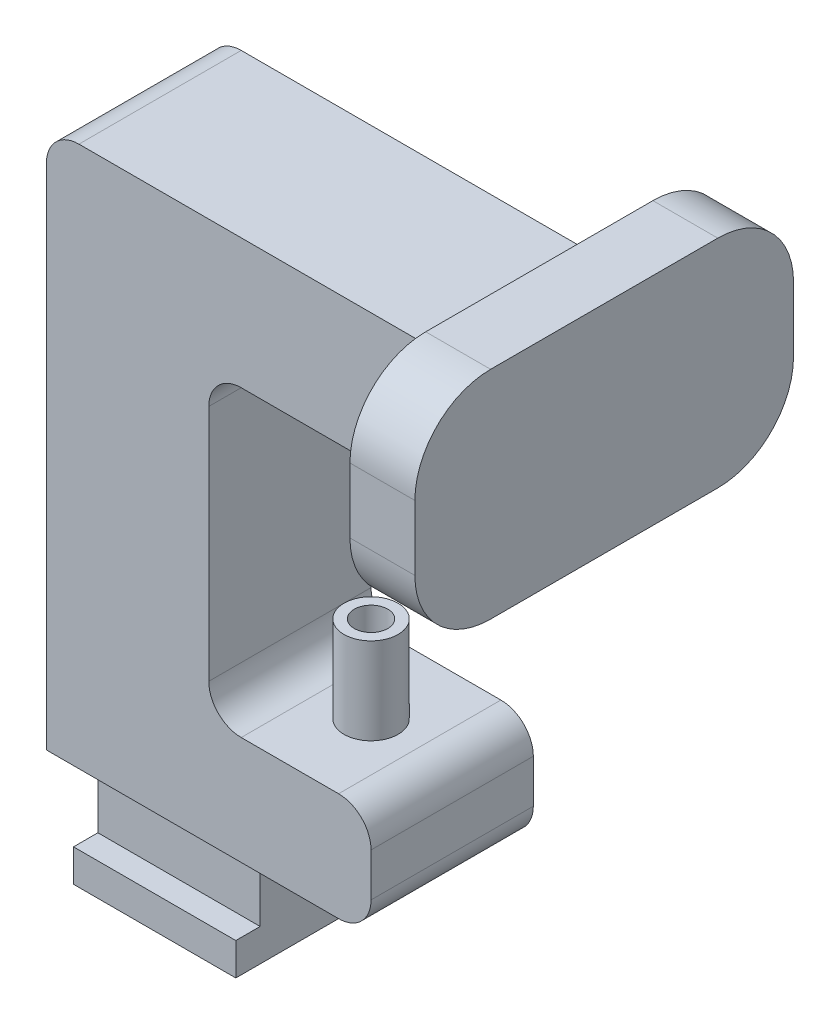
SolidWorks part; units mm, degrees
other "Markup1"
sketch "Sketch8" plane through (34.6, -62, 15) normal (0.0601, -0.0781, 0.9951) x (0.988, 0.1465, -0.0482)
ref_plane "Front Plane" through (0, 0, 0) normal (0, 0, 1) x (1, 0, 0)
ref_plane "Top Plane" through (0, 0, 0) normal (0, 1, 0) x (1, 0, 0)
ref_plane "Right Plane" through (0, 0, 0) normal (1, 0, 0) x (0, 0, -1)
sketch "Sketch1" plane through (0, 0, 0) normal (0, 0, 1) x (1, 0, 0)
  line L0 (0, 0) -> (0, -50)
  line L1 (0, -50) -> (25, -50)
  line L2 (10, 0) -> (10, -40)
  line L3 (10, -40) -> (25, -40)
  line L4 (0, 0) -> (10, 0)
  line L5 (25, -50) -> (25, -40)
  dimension "D1" = 50
  dimension "D2" = 25
  dimension "D3" = 10
extrude "Boss-Extrude1" add sketch "Sketch1" along normal blind 15
sketch "Sketch2" plane through (0, 0, 0) normal (-1, 0, 0) x (0, 0, 1)
  line L0 (7.5, 0) -> (7.5, -50) construction
  line L1 (15, 0) -> (0, 0) construction
  line L2 (15, -50) -> (0, -50) construction
  line L3 (10.25, -50) -> (4.75, -50)
  line L4 (4.75, -50) -> (4.75, -59)
  line L5 (4.75, -59) -> (2.5, -59)
  line L6 (2.5, -59) -> (2.5, -62)
  line L7 (2.5, -62) -> (8.2744, -62)
  line L8 (12.5, -62) -> (6.7256, -62)
  line L9 (10.25, -59) -> (12.5, -59)
  line L10 (12.5, -59) -> (12.5, -62)
  line L11 (10.25, -50) -> (10.25, -59)
  line M8 (0, -50) -> (15, -50)
  dimension "D1" = 5.5
  dimension "D2" = 10
  dimension "D3" = 3
  dimension "D4" = 9
extrude "Boss-Extrude2" add sketch "Sketch2" against normal blind 10 contours L11 L3 L4 L5 L6 L7 L8 L10 L9 M8
sketch "Sketch3" plane through (0, -40, 0) normal (0, 1, 0) x (1, 0, 0)
  line L0 (17.5, 0) -> (17.5, -15) construction
  line L1 (25, 0) -> (10, 0) construction
  line L2 (25, -15) -> (10, -15) construction
  line L3 (25, -7.5) -> (10, -7.5) construction
  line L4 (25, -15) -> (25, 0) construction
  line L5 (10, -15) -> (10, 0) construction
  circle A0 centre (17.5, -7.5) radius 1.55
  dimension "D1" = 3.1
extrude "Cut-Extrude1" cut sketch "Sketch3" against normal through all
sketch "Sketch4" plane through (0, -40, 0) normal (0, 1, 0) x (1, 0, 0)
  circle A0 centre (17.5, -7.5) radius 1.55 construction
  circle A1 centre (17.5, -7.5) radius 1.55
  circle A2 centre (17.5, -7.5) radius 2.5
  dimension "D1" = 5
extrude "Boss-Extrude3" add sketch "Sketch4" along normal blind 8
sketch "Sketch5" plane through (10, 0, 0) normal (1, 0, 0) x (0, 0, -1)
  line L0 (0, -40) -> (0, 0) construction
  line L1 (-15, 0) -> (0, 0)
  line L2 (-15, 0) -> (-15, -12)
  line L3 (-15, -12) -> (0, -12)
  line L4 (0, 0) -> (0, -12)
  dimension "D1" = 12
extrude "Boss-Extrude4" add sketch "Sketch5" along normal blind 23.05
sketch "Sketch7" plane through (0, 0, 0) normal (-1, 0, 0) x (0, 0, 1)
  line L12 (0, 0) -> (0, -50)
  line L13 (0, -50) -> (4.75, -50)
  line L14 (4.75, -50) -> (4.75, -59)
  line L15 (4.75, -59) -> (2.5, -59)
  line L16 (2.5, -59) -> (2.5, -62)
  line L17 (2.5, -62) -> (12.5, -62)
  line L18 (12.5, -62) -> (12.5, -59)
  line L19 (12.5, -59) -> (10.25, -59)
  line L20 (10.25, -59) -> (10.25, -50)
  line L21 (10.25, -50) -> (15, -50)
  line L22 (15, -50) -> (15, 0)
  line L23 (15, 0) -> (0, 0)
  line L24 (0, 0) -> (0, -50)
  line L25 (0, -50) -> (4.75, -50)
  line L26 (4.75, -50) -> (4.75, -59)
  line L27 (4.75, -59) -> (2.5, -59)
  line L28 (2.5, -59) -> (2.5, -62)
  line L29 (2.5, -62) -> (12.5, -62)
  line L30 (12.5, -62) -> (12.5, -59)
  line L31 (12.5, -59) -> (10.25, -59)
  line L32 (10.25, -59) -> (10.25, -50)
  line L33 (10.25, -50) -> (15, -50)
  line L34 (15, -50) -> (15, 0)
  line L35 (15, 0) -> (0, 0)
  dimension "D1" = 0
extrude "Boss-Extrude5" add sketch "Sketch7" along normal blind 5
sketch "Sketch9" plane through (33.05, 0, 0) normal (1, 0, 0) x (0, 0, -1)
  line L0 (-15, -6) -> (0, -6) construction
  line L1 (-15, 0) -> (-15, -12) construction
  line L2 (0, -12) -> (0, 0) construction
  line L4 (-25, -16) -> (10, -16)
  line L5 (-25, -16) -> (-25, 4)
  line L6 (-25, 4) -> (10, 4)
  line L7 (10, -16) -> (10, 4)
  line L8 (-25, -16) -> (10, 4) construction
  line L9 (-25, 4) -> (10, -16) construction
  point P6 (-7.5, -6)
  dimension "D1" = 35
  dimension "D2" = 20
extrude "Boss-Extrude6" add sketch "Sketch9" along normal blind 6
fillet "Fillet1" radius 7 4 edges at (36.05, -16, 25) (36.05, -16, -10) (36.05, 4, -10) (36.05, 4, 25)
fillet "Fillet4" radius 3 5 edges at (25, -50, 7.5) (25, -40, 7.5) (10, -40, 7.5) (10, -12, 7.5) (-5, 0, 7.5)
fillet "Fillet6" radius 1 4 edges at (33.05, -6, 15) (33.05, -6, 0) (33.05, 0, 7.5) (33.05, -12, 7.5)
